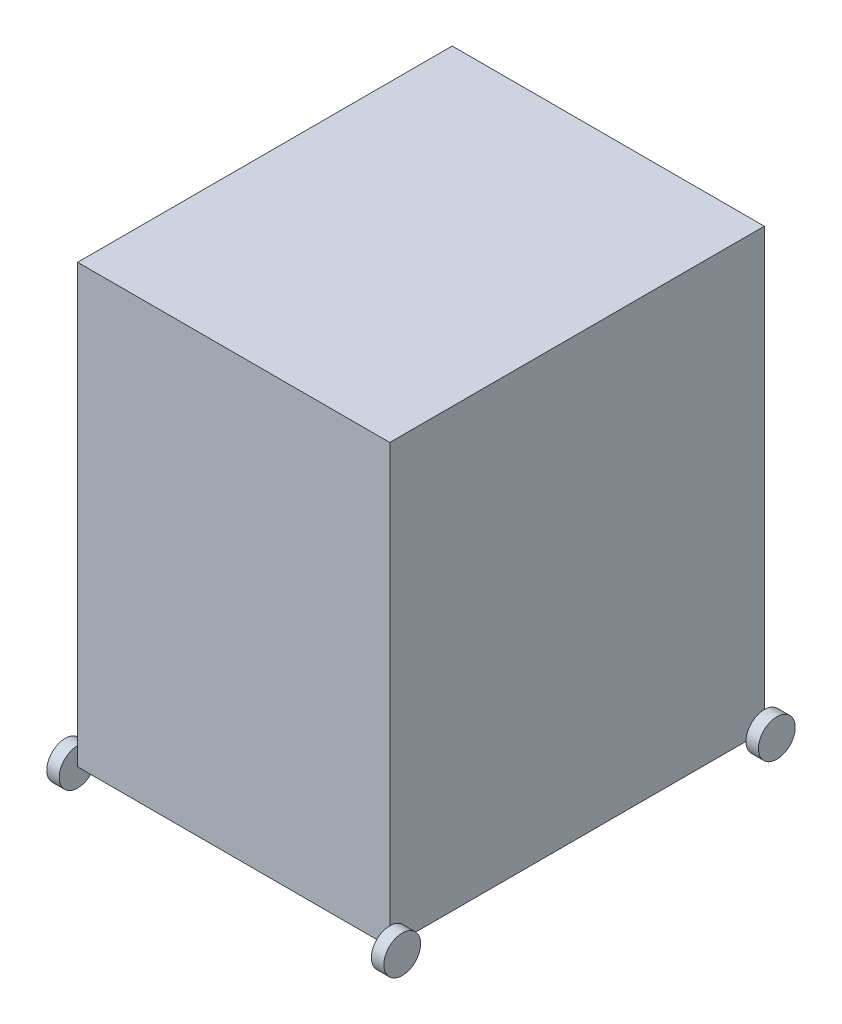
SolidWorks part; units mm, degrees
material "Maple"
ref_plane "Front Plane" through (0, 0, 0) normal (0, 0, 1) x (1, 0, 0)
ref_plane "Top Plane" through (0, 0, 0) normal (0, 1, 0) x (1, 0, 0)
ref_plane "Right Plane" through (0, 0, 0) normal (1, 0, 0) x (0, 0, -1)
sketch "Sketch1" plane through (0, 0, 0) normal (0, 1, 0) x (1, 0, 0)
  line L1 (-154.4444, -75.1576) -> (95.5556, -75.1576)
  line L2 (-154.4444, -75.1576) -> (-154.4444, 224.8424)
  line L3 (-154.4444, 224.8424) -> (95.5556, 224.8424)
  line L4 (95.5556, -75.1576) -> (95.5556, 224.8424)
  dimension "D1" = 250
  dimension "D2" = 300
extrude "Boss-Extrude1" add sketch "Sketch1" along normal blind 350
sketch "Sketch2" plane through (95.5556, 0, 0) normal (1, 0, 0) x (0, 0, -1)
  line L0 (-75.1576, 0) -> (224.8424, 0) construction
  circle A0 centre (-75.1576, 0) radius 14.75
  circle A1 centre (224.8424, 0) radius 14.75
  dimension "D1" = 29.5
  dimension "D2" = 29.5
extrude "Boss-Extrude2" add sketch "Sketch2" along normal blind 10
pattern_linear "LPattern2" count 2 spacing 260 along (-1, 0, 0) of "Boss-Extrude2"
